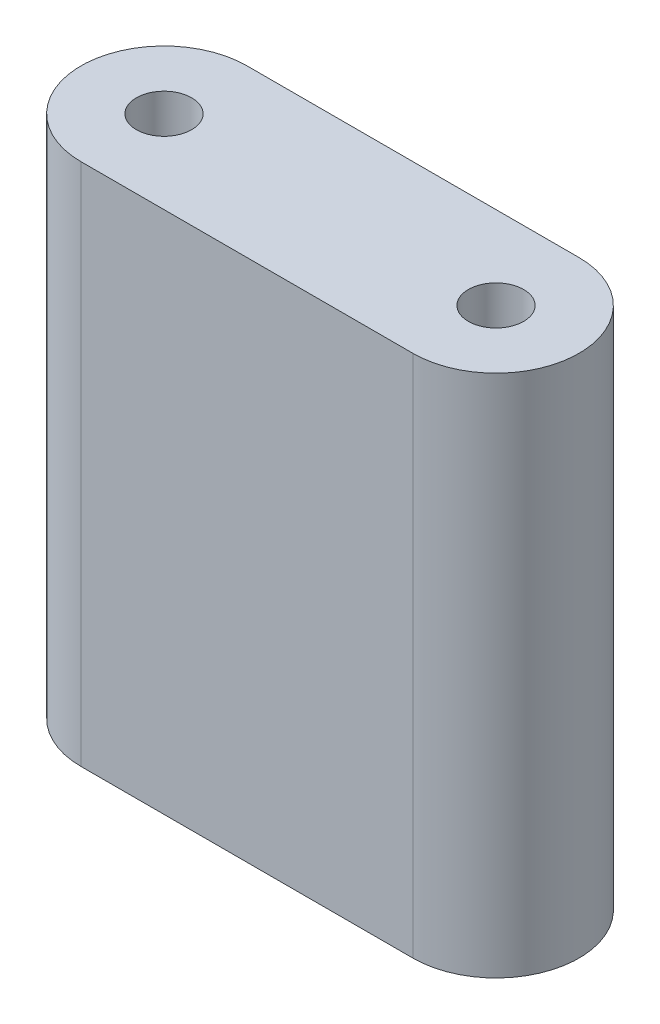
SolidWorks part; units mm, degrees
material "ABS"
ref_plane "Front Plane" through (0, 0, 0) normal (0, 0, 1) x (1, 0, 0)
ref_plane "Top Plane" through (0, 0, 0) normal (0, 1, 0) x (1, 0, 0)
ref_plane "Right Plane" through (0, 0, 0) normal (1, 0, 0) x (0, 0, -1)
sketch "Sketch1" plane through (0, 0, 0) normal (0, 1, 0) x (1, 0, 0)
  line L0 (-12, 0) -> (12, 0) construction
  line L1 (-12, 0) -> (12, 0) construction
  line L2 (-12, 6) -> (12, 6)
  line L3 (-12, -6) -> (12, -6)
  circle A0 centre (-12, 0) radius 2
  circle A1 centre (12, 0) radius 2
  arc A2 (-12, 6) -> (-12, -6) centre (-12, 0) ccw
  arc A3 (12, -6) -> (12, 6) centre (12, 0) ccw
  point P6 (0, 0)
  dimension "D2" = 4
  dimension "D3" = 4
  dimension "D1" = 24
extrude "Boss-Extrude1" add sketch "Sketch1" along normal blind 37.86
sketch "Sketch2" plane through (0, 0, 0) normal (0, -1, 0) x (1, 0, 0)
  line L1 (-13.8331, 3.175) -> (-15.6662, 0)
  line L2 (-15.6662, 0) -> (-13.8331, -3.175)
  line L3 (-13.8331, -3.175) -> (-10.1669, -3.175)
  line L4 (-10.1669, -3.175) -> (-8.3338, 0)
  line L5 (-8.3338, 0) -> (-10.1669, 3.175)
  line L6 (-10.1669, 3.175) -> (-13.8331, 3.175)
  circle A0 centre (-12, 0) radius 3.175 construction
  dimension "D1" = 6.35
extrude "Cut-Extrude1" cut sketch "Sketch2" against normal offset from surface (28.86 mm away) 9 up to face at (-12, 37.86, 2)
mirror "Mirror1" about plane through (0, 0, 0) normal (1, 0, 0) of "Cut-Extrude1"
